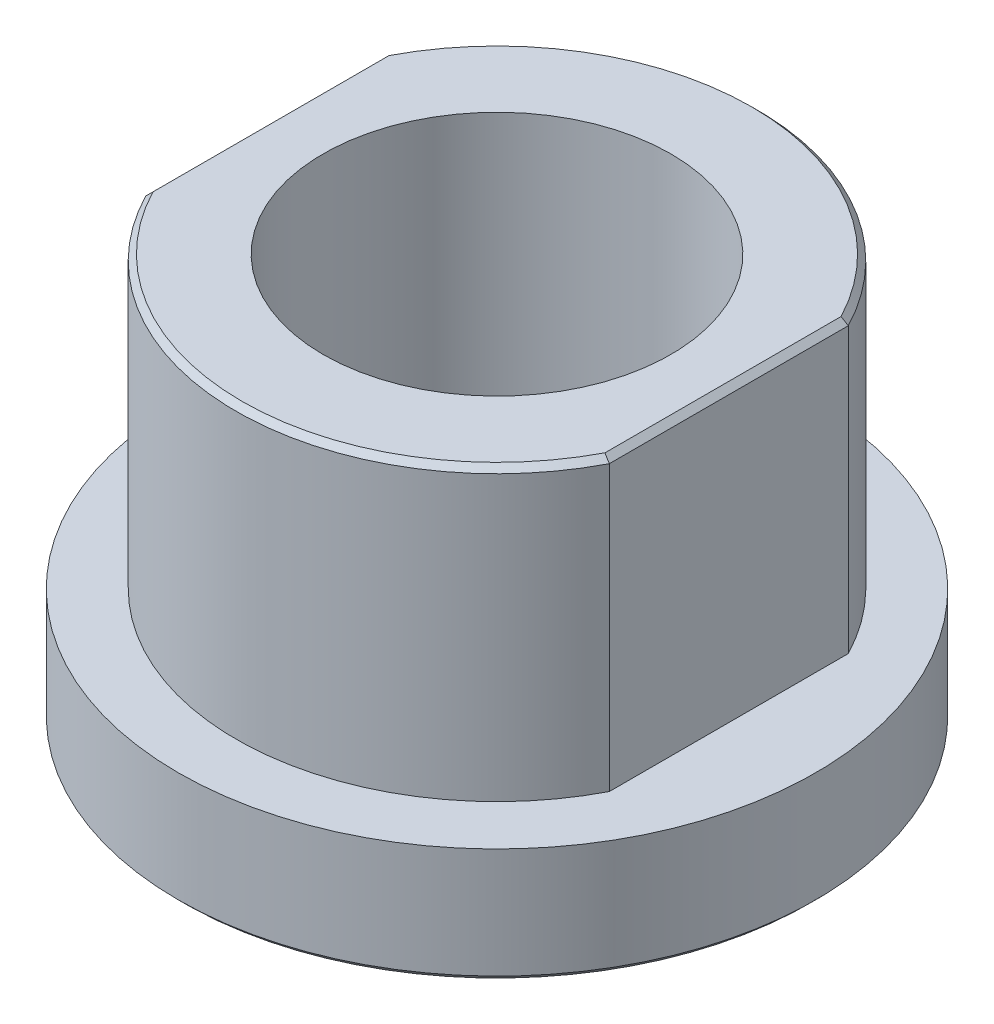
SolidWorks part; units mm, degrees
material "Brass"
ref_plane "Front Plane" through (0, 0, 0) normal (0, 0, 1) x (1, 0, 0)
ref_plane "Top Plane" through (0, 0, 0) normal (0, 1, 0) x (1, 0, 0)
ref_plane "Right Plane" through (0, 0, 0) normal (1, 0, 0) x (0, 0, -1)
sketch "Sketch1" plane through (0, 0, 0) normal (0, 0, 1) x (1, 0, 0)
  line L0 (3, 0) -> (5.5, 0)
  line L1 (5.5, 0) -> (5.5, 2)
  line L2 (5.5, 2) -> (4.5, 2)
  line L3 (4.5, 2) -> (4.5, 7)
  line L4 (4.5, 7) -> (3, 7)
  line L5 (3, 7) -> (3, 0)
  line L6 (0, 0) -> (0, 3.7735) construction
  dimension "D1" = 4.5
  dimension "D2" = 3
  dimension "D3" = 5.5
  dimension "D4" = 2
  dimension "D5" = 7
revolve "Revolve1" add sketch "Sketch1" angle 360 about L6
sketch "Sketch2" plane through (0, 7, 0) normal (0, 1, 0) x (1, 0, 0)
  line L2 (-4, 2.0616) -> (-4, -2.0616)
  line L4 (4, 2.0616) -> (4, -2.0616)
  circle A0 centre (0, 0) radius 4.5 construction
  circle A1 centre (0, 0) radius 4.5 construction
  arc A2 (-4, 2.0616) -> (-4, -2.0616) centre (0, 0) ccw
  arc A3 (4, -2.0616) -> (4, 2.0616) centre (0, 0) ccw
  dimension "D1" = 8
extrude "Cut-Extrude1" cut sketch "Sketch2" against normal up to surface (5 mm away) and the other way through all up to face at (0, 2, -4.5)
chamfer "Chamfer1" distance 0.1 angle 45 5 edges at (0, 0, -5.5) (0, 7, 4.5) (0, 7, -4.5) (4, 7, 0) (-4, 7, 0)
